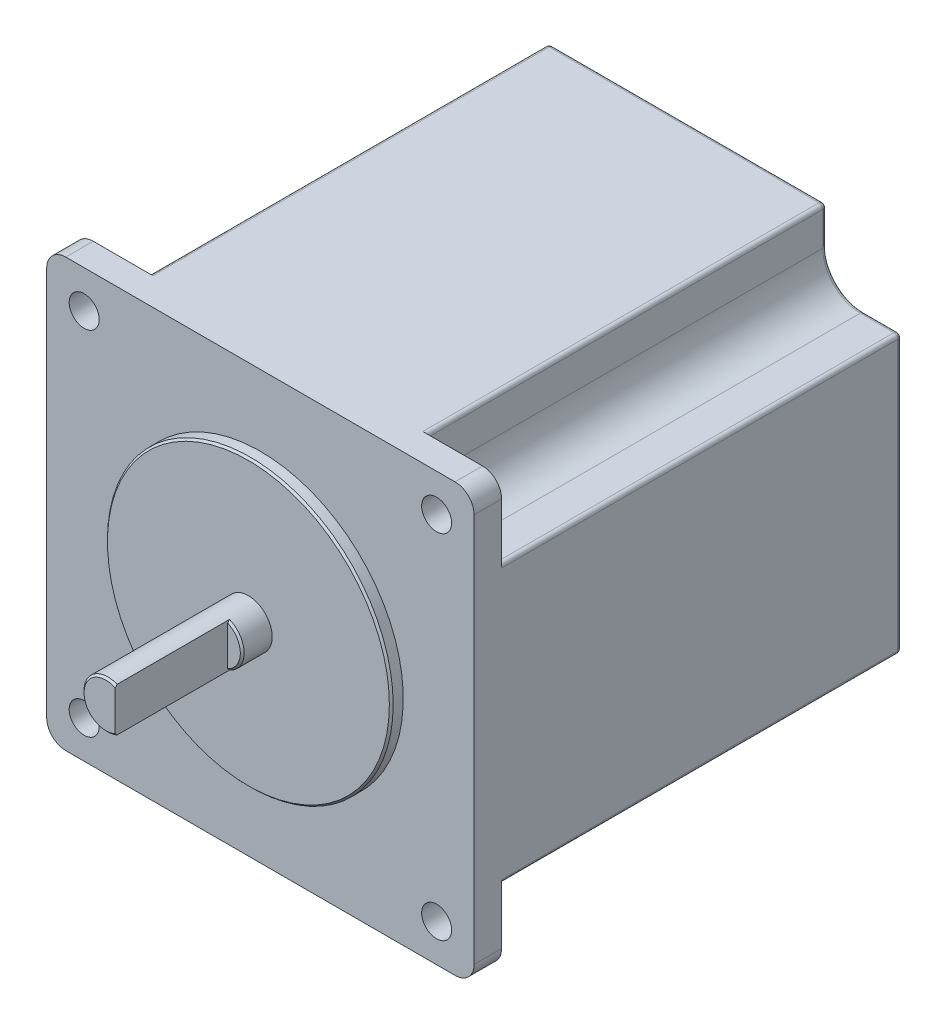
SolidWorks part; units mm, degrees
ref_plane "Front Plane" through (0, 0, 0) normal (0, 0, 1) x (1, 0, 0)
ref_plane "Top Plane" through (0, 0, 0) normal (0, 1, 0) x (1, 0, 0)
ref_plane "Right Plane" through (0, 0, 0) normal (1, 0, 0) x (0, 0, -1)
sketch "Sketch1" plane through (0, 0, 0) normal (0, 0, 1) x (1, 0, 0)
  line L1 (-28.5, -28.5) -> (28.5, -28.5)
  line L2 (-28.5, -28.5) -> (-28.5, 28.5)
  line L3 (-28.5, 28.5) -> (28.5, 28.5)
  line L4 (28.5, -28.5) -> (28.5, 28.5)
  line L5 (-28.5, -28.5) -> (28.5, 28.5) construction
  line L6 (-28.5, 28.5) -> (28.5, -28.5) construction
  point P0 (0, 0)
  dimension "D1" = 57
  dimension "D2" = 57
extrude "Boss-Extrude1" add sketch "Sketch1" along normal blind 57
sketch "Sketch2" plane through (0, 0, 57) normal (0, 0, 1) x (1, 0, 0)
  line L0 (-28.5, 28.5) -> (28.5, -28.5) construction
  line L2 (-23.5, -23.5) -> (23.5, -23.5) construction
  line L3 (-23.5, -23.5) -> (-23.5, 23.5) construction
  line L4 (-23.5, 23.5) -> (23.5, 23.5) construction
  line L5 (23.5, -23.5) -> (23.5, 23.5) construction
  line L6 (-23.5, -23.5) -> (23.5, 23.5) construction
  line L7 (-23.5, 23.5) -> (23.5, -23.5) construction
  circle A0 centre (-23.5, 23.5) radius 2
  circle A1 centre (23.5, 23.5) radius 2
  circle A2 centre (23.5, -23.5) radius 2
  circle A3 centre (-23.5, -23.5) radius 2
  point P4 (0, 0)
  dimension "D2" = 4
  dimension "D1" = 47
extrude "Cut-Extrude1" cut sketch "Sketch2" against normal through all
sketch "Sketch8" plane through (0, 0, 0) normal (0, 0, -1) x (-1, 0, 0)
  line L0 (18.5, -28.5) -> (18.5, -23.5)
  line L1 (28.5, -28.5) -> (-28.5, -28.5) construction
  line L2 (23.5, -18.5) -> (28.5, -18.5)
  line L3 (28.5, 28.5) -> (28.5, -28.5) construction
  line L4 (23.5, 18.5) -> (28.5, 18.5)
  line L5 (18.5, 23.5) -> (18.5, 28.5)
  line L6 (-28.5, 28.5) -> (28.5, 28.5) construction
  line L7 (-18.5, 23.5) -> (-18.5, 28.5)
  line L8 (-23.5, 18.5) -> (-28.5, 18.5)
  line L9 (-28.5, -28.5) -> (-28.5, 28.5) construction
  line L10 (-23.5, -18.5) -> (-28.5, -18.5)
  line L11 (-18.5, -23.5) -> (-18.5, -28.5)
  line L12 (28.5, -18.5) -> (28.5, -28.5)
  line L13 (28.5, -28.5) -> (18.5, -28.5)
  line L14 (-18.5, -28.5) -> (-28.5, -28.5)
  line L15 (-28.5, -18.5) -> (-28.5, -28.5)
  line L16 (-28.5, 18.5) -> (-28.5, 28.5)
  line L17 (-28.5, 28.5) -> (-18.5, 28.5)
  line L18 (18.5, 28.5) -> (28.5, 28.5)
  line L19 (28.5, 28.5) -> (28.5, 18.5)
  arc A0 (23.5, -18.5) -> (18.5, -23.5) centre (23.5, -23.5) ccw
  arc A1 (-18.5, -23.5) -> (-23.5, -18.5) centre (-23.5, -23.5) ccw
  arc A2 (-23.5, 18.5) -> (-18.5, 23.5) centre (-23.5, 23.5) ccw
  arc A3 (18.5, 23.5) -> (23.5, 18.5) centre (23.5, 23.5) ccw
  circle A4 centre (23.5, 23.5) radius 2 construction
extrude "Cut-Extrude4" cut sketch "Sketch8" against normal blind 53.34
fillet "Fillet1" radius 2.54 4 edges at (-28.5, -28.5, 55.17) (28.5, -28.5, 55.17) (28.5, 28.5, 55.17) (-28.5, 28.5, 55.17)
sketch "Sketch9" plane through (0, 0, 57) normal (0, 0, 1) x (1, 0, 0)
  line L0 (0, -28.5) -> (0, 28.5) construction
  line L1 (-25.96, -28.5) -> (25.96, -28.5) construction
  line L2 (25.96, 28.5) -> (-25.96, 28.5) construction
  circle A0 centre (0, 0) radius 19.05
  dimension "D1" = 38.1
extrude "Boss-Extrude2" add sketch "Sketch9" along normal blind 1.6
sketch "Sketch10" plane through (0, 0, 58.6) normal (0, 0, 1) x (1, 0, 0)
  line L0 (0, 0) -> (0, -19.05) construction
  circle A0 centre (0, 0) radius 19.05 construction
  circle A1 centre (0, 0) radius 3.175
  dimension "D1" = 6.35
extrude "Boss-Extrude3" add sketch "Sketch10" along normal blind 19
sketch "Sketch11" plane through (0, 0, 77.6) normal (0, 0, 1) x (1, 0, 0)
  line L0 (1.2349, -2.925) -> (1.2349, 2.925)
  circle A0 centre (0, 0) radius 3.175 construction
  arc A1 (1.2349, -2.925) -> (1.2349, 2.925) centre (0, 0) ccw
  dimension "D1" = 5.85
extrude "Cut-Extrude5" cut sketch "Sketch11" against normal blind 15
chamfer "Chamfer1" distance 0.254 angle 45 3 edges at (19.05, 0, 58.6) (3.175, 0, 62.6) (-3.175, 0, 77.6)
fillet "Fillet2" radius 0.508 24 edges at (28.5, 0, 0) (26, 18.5, 0) (19.9645, 19.9645, 0) (18.5, 26, 0) (0, 28.5, 0) (-18.5, 26, 0) (-19.9645, 19.9645, 0) (-26, 18.5, 0) (-28.5, 0, 0) (-26, -18.5, 0) (-19.9645, -19.9645, 0) (-18.5, -26, 0) (0, -28.5, 0) (18.5, -26, 0) (19.9645, -19.9645, 0) (26, -18.5, 0) (-18.5, 28.5, 26.67) (-28.5, 18.5, 26.67) (28.5, 18.5, 26.67) (18.5, 28.5, 26.67) (28.5, -18.5, 26.67) (18.5, -28.5, 26.67) (-18.5, -28.5, 26.67) (-28.5, -18.5, 26.67)
